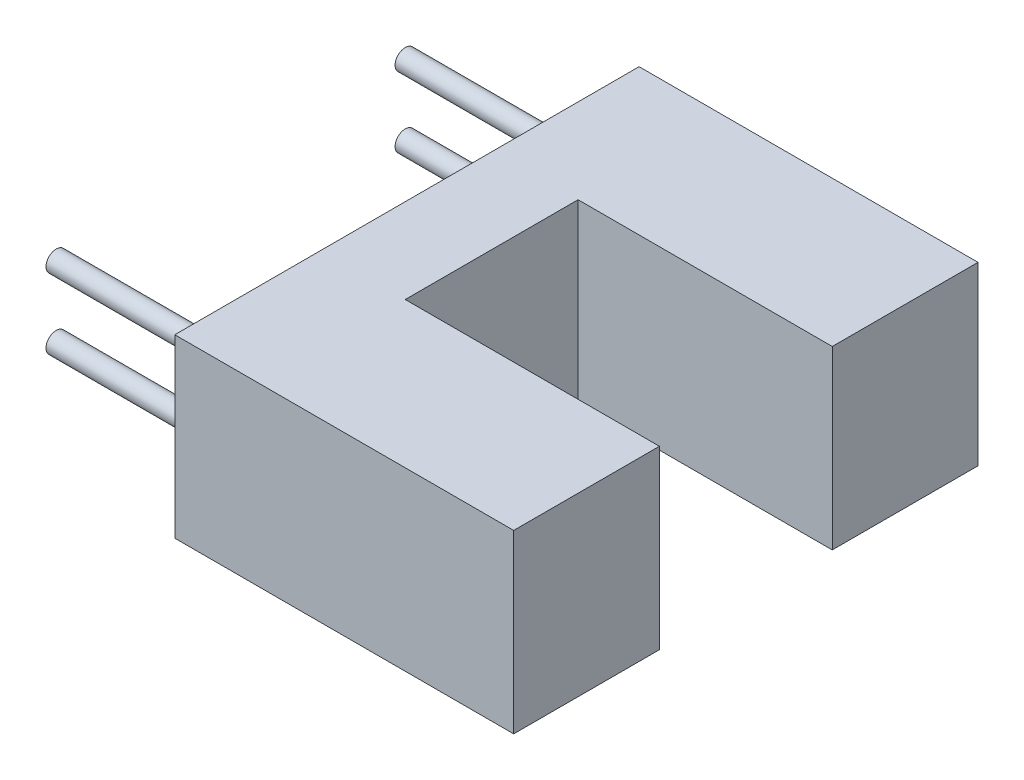
SolidWorks part; units mm, degrees
ref_plane "Front Plane" through (0, 0, 0) normal (0, 0, 1) x (1, 0, 0)
ref_plane "Top Plane" through (0, 0, 0) normal (0, 1, 0) x (1, 0, 0)
ref_plane "Right Plane" through (0, 0, 0) normal (1, 0, 0) x (0, 0, -1)
sketch "Sketch1" plane through (0, 0, 0) normal (0, 1, 0) x (1, 0, 0)
  line L0 (0, 0) -> (0, 13.7)
  line L1 (0, 13.7) -> (10, 13.7)
  line L2 (10, 13.7) -> (10, 9.4)
  line L3 (10, 9.4) -> (2.5, 9.4)
  line L4 (2.5, 9.4) -> (2.5, 4.3)
  line L5 (2.5, 4.3) -> (10, 4.3)
  line L6 (10, 4.3) -> (10, 0)
  line L7 (10, 0) -> (0, 0)
  line L8 (0, 6.85) -> (2.5, 6.85) construction
  dimension "D1" = 13.7
  dimension "D2" = 4.3
  dimension "D3" = 2.5
  dimension "D4" = 10
extrude "Boss-Extrude1" add sketch "Sketch1" along normal blind 5.2
sketch "Sketch2" plane through (0, 0, 0) normal (-1, 0, 0) x (0, 0, 1)
  line L0 (-13.7, 5.2) -> (-13.7, 0) construction
  line L1 (-12, 1.56) -> (-1.7, 1.56) construction
  line L2 (-12, 1.56) -> (-12, 3.64) construction
  line L3 (-12, 3.64) -> (-1.7, 3.64) construction
  line L4 (-1.7, 1.56) -> (-1.7, 3.64) construction
  line L5 (-13.7, 5.2) -> (0, 5.2) construction
  line L6 (-13.7, 2.6) -> (-12, 2.6) construction
  line L7 (-6.85, 5.2) -> (-6.85, 3.64) construction
  circle A0 centre (-12, 3.64) radius 0.3
  circle A1 centre (-1.7, 3.64) radius 0.3
  circle A2 centre (-1.7, 1.56) radius 0.3
  circle A3 centre (-12, 1.56) radius 0.3
  dimension "D1" = 0.6
  dimension "D2" = 1.7
  dimension "D3" = 1.56
extrude "Boss-Extrude2" add sketch "Sketch2" along normal blind 5.2
